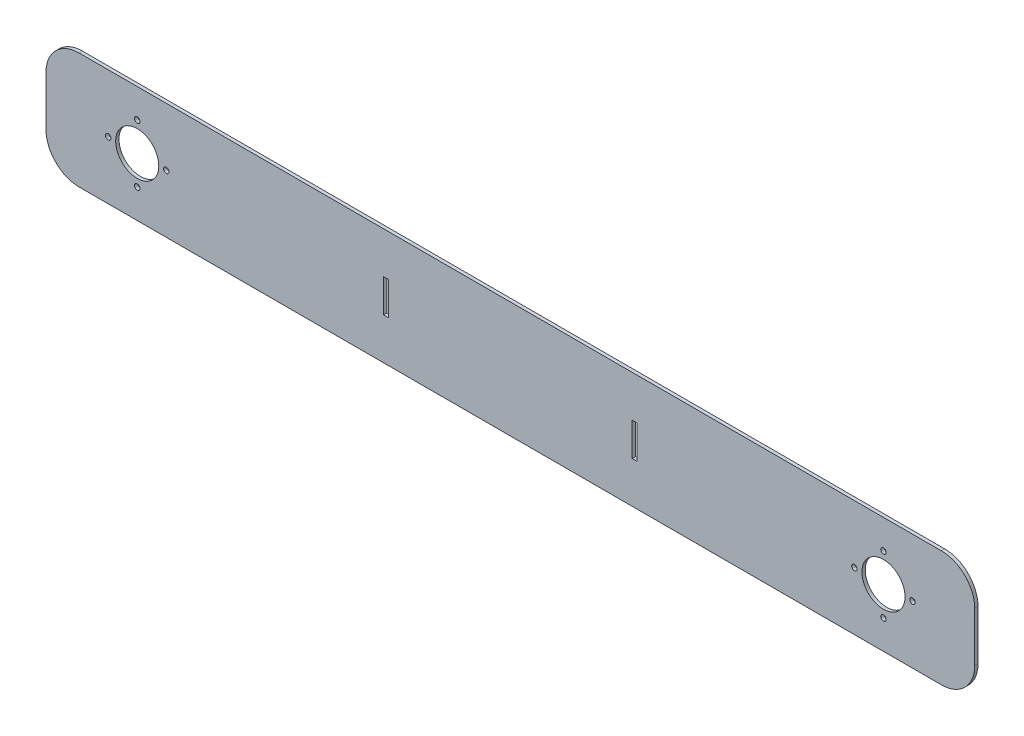
SolidWorks part; units mm, degrees
ref_plane "Front" through (0, 0, 0) normal (0, 0, 1) x (1, 0, 0)
ref_plane "Top" through (0, 0, 0) normal (0, 1, 0) x (1, 0, 0)
ref_plane "Right" through (0, 0, 0) normal (1, 0, 0) x (0, 0, -1)
sketch "草图2" plane through (0, 0, 0) normal (0, 0, 1) x (1, 0, 0)
  line L1 (-280, 50) -> (280, 50)
  line L2 (-300, 30) -> (-300, -30)
  line L3 (-280, -50) -> (280, -50)
  line L4 (300, 30) -> (300, -30)
  line L5 (-300, 50) -> (300, -50) construction
  line L6 (-300, -50) -> (300, 50) construction
  arc A0 (-300, -30) -> (-280, -50) centre (-280, -30) ccw
  arc A1 (-300, 30) -> (-280, 50) centre (-280, 30) cw
  arc A2 (300, -30) -> (280, -50) centre (280, -30) cw
  arc A3 (300, 30) -> (280, 50) centre (280, 30) ccw
  point P0 (0, 0)
  dimension "D3" = 20
  dimension "D1" = 600
  dimension "D2" = 100
extrude "凸台-拉伸1" add sketch "草图2" along normal blind 2
sketch "草图3" plane through (0, 0, 2) normal (0, 0, 1) x (1, 0, 0)
  line L0 (-300, 30) -> (-300, -30) construction
  circle A0 centre (-225, 0) radius 13
  circle A1 centre (225, 0) radius 13
  circle A2 centre (-242.5, 0) radius 1.65
  circle A3 centre (-207.5, 0) radius 1.65
  circle A4 centre (-225, 17.5) radius 1.65
  circle A5 centre (-225, -17.5) radius 1.65
  circle A6 centre (242.5, 0) radius 1.65
  circle A7 centre (225, 17.5) radius 1.65
  circle A8 centre (207.5, 0) radius 1.65
  circle A9 centre (225, -17.5) radius 1.65
  point P7 (-300, 0)
  dimension "D1" = 450
  dimension "D3" = 26
  dimension "D4" = 26
  dimension "D5" = 17.5
  dimension "D13" = 3.3
  dimension "D14" = 3.3
  dimension "D15" = 3.3
  dimension "D16" = 3.3
  dimension "D17" = 3.3
  dimension "D18" = 3.3
  dimension "D19" = 3.3
  dimension "D20" = 3.3
  dimension "D2" = 75
  dimension "D6" = 17.5
  dimension "D7" = 17.5
  dimension "D8" = 17.5
  dimension "D9" = 17.5
  dimension "D10" = 17.5
  dimension "D11" = 17.5
  dimension "D12" = 17.5
extrude "切除-拉伸1" cut sketch "草图3" against normal up to next
sketch "草图6" plane through (0, 0, 2) normal (0, 0, 1) x (1, 0, 0)
  line L1 (-386.9469, 35) -> (386.9469, 35)
  line L2 (-386.9469, 35) -> (-386.9469, -35)
  line L3 (-386.9469, -35) -> (386.9469, -35)
  line L4 (386.9469, 35) -> (386.9469, -35)
  line L5 (-386.9469, 35) -> (386.9469, -35) construction
  line L6 (-386.9469, -35) -> (386.9469, 35) construction
  point P0 (0, 0)
  dimension "D1" = 70
extrude "切除-拉伸4" cut sketch "草图6" against normal blind 10 flip side to cut contours L1 L4 L3 L2
sketch "草图7" plane through (0, 0, 2) normal (0, 0, 1) x (1, 0, 0)
  line L0 (-300, 30) -> (-300, -30) construction
  line L1 (-320, 62.6261) -> (-280, 62.6261)
  line L2 (-320, 62.6261) -> (-320, -62.6261)
  line L3 (-320, -62.6261) -> (-280, -62.6261)
  line L4 (-280, 62.6261) -> (-280, -62.6261)
  line L5 (-320, 62.6261) -> (-280, -62.6261) construction
  line L6 (-320, -62.6261) -> (-280, 62.6261) construction
  line L7 (300, -30) -> (300, 30) construction
  line L8 (280, 58.1577) -> (320, 58.1577)
  line L9 (280, 58.1577) -> (280, -58.1577)
  line L10 (280, -58.1577) -> (320, -58.1577)
  line L11 (320, 58.1577) -> (320, -58.1577)
  line L12 (280, 58.1577) -> (320, -58.1577) construction
  line L13 (280, -58.1577) -> (320, 58.1577) construction
  point P0 (-300, 0)
  point P7 (300, 0)
  dimension "D1" = 40
  dimension "D2" = 40
extrude "切除-拉伸5" cut sketch "草图7" against normal blind 10
fillet "圆角1" radius 20 4 edges at (280, -35, 1) (280, 35, 1) (-280, -35, 1) (-280, 35, 1)
sketch "草图10" plane through (0, 0, 2) normal (0, 0, 1) x (1, 0, 0)
  line L0 (-260, -35) -> (260, -35) construction
  line L1 (-76.5, 10) -> (-73.5, 10)
  line L2 (-76.5, 10) -> (-76.5, -10)
  line L3 (-76.5, -10) -> (-73.5, -10)
  line L4 (-73.5, 10) -> (-73.5, -10)
  line L5 (-76.5, 10) -> (-73.5, -10) construction
  line L6 (-76.5, -10) -> (-73.5, 10) construction
  line L7 (73.5, 10) -> (76.5, 10)
  line L8 (73.5, 10) -> (73.5, -10)
  line L9 (73.5, -10) -> (76.5, -10)
  line L10 (76.5, 10) -> (76.5, -10)
  line L11 (73.5, 10) -> (76.5, -10) construction
  line L12 (73.5, -10) -> (76.5, 10) construction
  circle A0 centre (-225, 0) radius 13 construction
  circle A1 centre (225, 0) radius 13 construction
  point P0 (-75, 0)
  point P5 (75, 0)
  dimension "D7" = 150
  dimension "D1" = 3
  dimension "D2" = 3
  dimension "D3" = 20
  dimension "D4" = 35
  dimension "D5" = 20
  dimension "D6" = 35
  dimension "D8" = 150
extrude "切除-拉伸6" cut sketch "草图10" against normal blind 10
